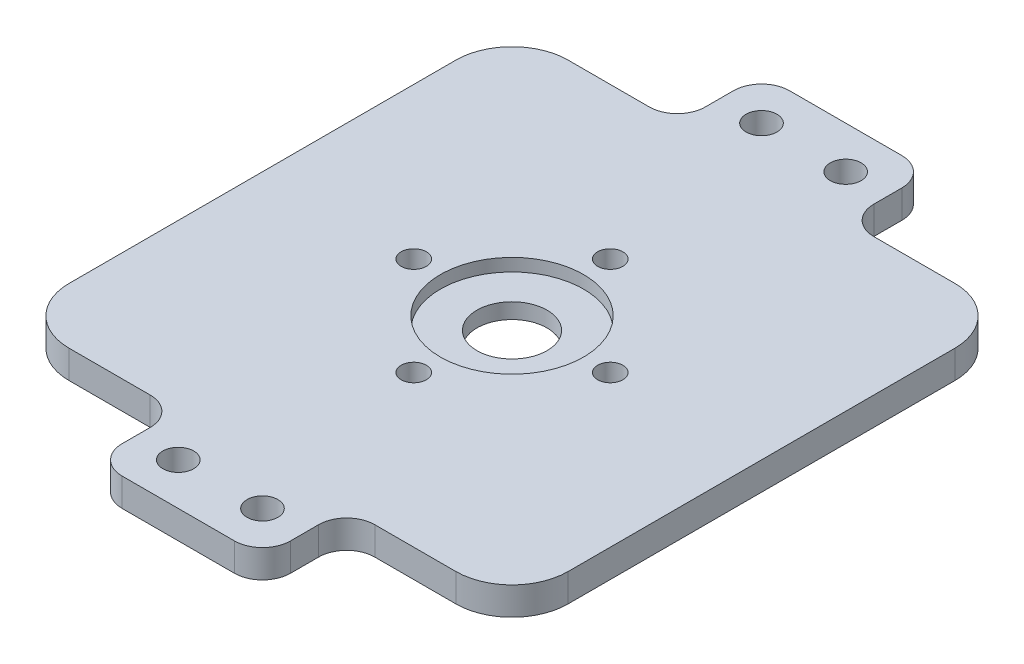
SolidWorks part; units mm, degrees
ref_plane "Front Plane" through (0, 0, 0) normal (0, 0, 1) x (1, 0, 0)
ref_plane "Top Plane" through (0, 0, 0) normal (0, 1, 0) x (1, 0, 0)
ref_plane "Right Plane" through (0, 0, 0) normal (1, 0, 0) x (0, 0, -1)
sketch "Sketch1" plane through (0, 0, 0) normal (0, 1, 0) x (1, 0, 0)
  line L1 (0, 0) -> (88.9, 0)
  line L2 (0, 0) -> (0, 88.9)
  line L3 (0, 88.9) -> (88.9, 88.9)
  line L4 (88.9, 0) -> (88.9, 88.9)
  line L5 (44.45, 88.9) -> (59.45, 88.9)
  line L6 (44.45, 88.9) -> (44.45, 103.9)
  line L7 (44.45, 103.9) -> (59.45, 103.9)
  line L8 (59.45, 88.9) -> (59.45, 103.9)
  line L9 (44.45, 88.9) -> (29.45, 88.9)
  line L10 (44.45, 88.9) -> (44.45, 103.9)
  line L11 (44.45, 103.9) -> (29.45, 103.9)
  line L12 (29.45, 88.9) -> (29.45, 103.9)
  line L13 (44.45, 0) -> (59.45, 0)
  line L14 (44.45, 0) -> (44.45, -15)
  line L15 (44.45, -15) -> (59.45, -15)
  line L16 (59.45, 0) -> (59.45, -15)
  line L17 (44.45, 0) -> (29.45, 0)
  line L18 (44.45, 0) -> (44.45, -15)
  line L19 (44.45, -15) -> (29.45, -15)
  line L20 (29.45, 0) -> (29.45, -15)
  circle A0 centre (44.45, 44.45) radius 17.5
  circle A1 centre (44.45, 61.95) radius 2.25
  circle A2 centre (61.95, 44.45) radius 2.25
  circle A3 centre (26.95, 44.45) radius 2.25
  circle A4 centre (44.45, 26.95) radius 2.25
  circle A5 centre (44.45, 44.45) radius 6.25
  circle A6 centre (36.95, 96.4) radius 2.75
  circle A7 centre (51.95, 96.4) radius 2.75
  circle A8 centre (36.95, -7.5) radius 2.75
  circle A9 centre (51.95, -7.5) radius 2.75
  dimension "D3" = 15
  dimension "D11" = 7.5
  dimension "D1" = 88.9
  dimension "D2" = 88.9
  dimension "D4" = 15
  dimension "D5" = 15
  dimension "D6" = 15
  dimension "D7" = 15
  dimension "D8" = 15
  dimension "D9" = 15
  dimension "D10" = 15
  dimension "D12" = 7.5
  dimension "D13" = 7.5
  dimension "D14" = 7.5
  dimension "D15" = 7.5
  dimension "D16" = 7.5
  dimension "D17" = 7.5
  dimension "D18" = 7.5
extrude "Boss-Extrude1" add sketch "Sketch1" along normal blind 5 contours L1 L4 L3 L2 A4 A0 A3 A1 A2 | A4 A0 A2 A1 A3 A5 | L1 L20 L19 L14 A8 | L16 L1 L14 L15 A9 | L12 L3 L6 L11 A6 | L3 L8 L7 L6 A7
fillet "Fillet1" radius 10 4 edges at (88.9, 2.5, -88.9) (88.9, 2.5, 0) (0, 2.5, 0) (0, 2.5, -88.9)
fillet "Fillet2" radius 5 8 edges at (29.45, 2.5, -103.9) (29.45, 2.5, -88.9) (59.45, 2.5, -103.9) (59.45, 2.5, -88.9) (29.45, 2.5, 15) (29.45, 2.5, 0) (59.45, 2.5, 0) (59.45, 2.5, 15)
sketch "Sketch2" plane through (0, 5, 0) normal (0, 1, 0) x (1, 0, 0)
  circle A0 centre (44.45, 44.45) radius 12.75
extrude "Cut-Extrude1" cut sketch "Sketch2" against normal blind 2.25
